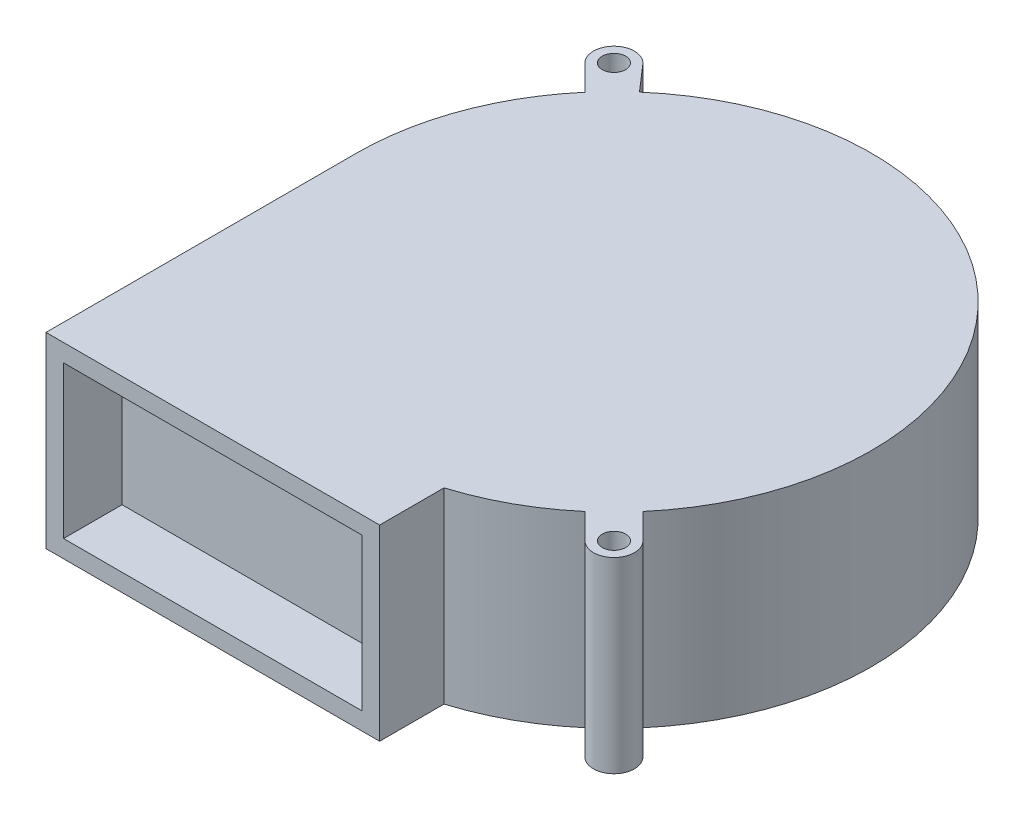
SolidWorks part; units mm, degrees
ref_plane "Alzado" through (0, 0, 0) normal (0, 0, 1) x (1, 0, 0)
ref_plane "Planta" through (0, 0, 0) normal (0, 1, 0) x (1, 0, 0)
ref_plane "Vista lateral" through (0, 0, 0) normal (1, 0, 0) x (0, 0, -1)
sketch "Croquis1" plane through (0, 0, 0) normal (0, 1, 0) x (1, 0, 0)
  line L0 (-35.3553, 35.3553) -> (35.3553, -35.3553) construction
  line L1 (0, 0) -> (44, 0) construction
  line L2 (-37.8302, 32.8805) -> (-33.489, 28.5392)
  line L3 (-32.7133, 37.6509) -> (-28.8585, 33.2143)
  line L4 (32.8805, -37.8302) -> (28.5392, -33.489)
  line L5 (37.8302, -32.8805) -> (33.489, -28.5392)
  line L6 (-44, 0) -> (-44, -53.0357)
  line L7 (-44, -53.0357) -> (13, -53.0357)
  line L8 (13, -53.0357) -> (13, -42.0357)
  arc A0 (-33.489, 28.5392) -> (-44, 0) centre (0, 0) ccw
  circle A1 centre (-35.3553, 35.3553) radius 2
  circle A2 centre (35.3553, -35.3553) radius 2
  arc A3 (-32.7133, 37.6509) -> (-37.8302, 32.8805) centre (-35.3553, 35.3553) ccw
  arc A4 (32.8805, -37.8302) -> (37.8302, -32.8805) centre (35.3553, -35.3553) ccw
  arc A5 (33.489, -28.5392) -> (-28.8585, 33.2143) centre (0, 0) ccw
  arc A6 (13, -42.0357) -> (28.5392, -33.489) centre (0, 0) ccw
  point P8 (0, 0)
  dimension "D1" = 88
  dimension "D3" = 4
  dimension "D5" = 7
  dimension "D2" = 100
  dimension "D4" = 45
  dimension "D6" = 57
  dimension "D7" = 11
extrude "Saliente-Extruir1" add sketch "Croquis1" along normal blind 32
sketch "Croquis2" plane through (0, 0, 53.0357) normal (0, 0, 1) x (1, 0, 0)
  line L0 (-44, 32) -> (-44, 0) construction
  line L1 (-41, 29) -> (10, 29)
  line L2 (-41, 29) -> (-41, 3)
  line L3 (-41, 3) -> (10, 3)
  line L4 (10, 29) -> (10, 3)
  line L6 (-44, 32) -> (13, 32) construction
  point P6 (-44, 16)
  point P7 (-41, 16)
  point P8 (-15.5, 29)
  point P11 (-15.5, 32)
  dimension "D1" = 26
  dimension "D2" = 3
extrude "Cortar-Extruir1" cut sketch "Croquis2" against normal blind 10
